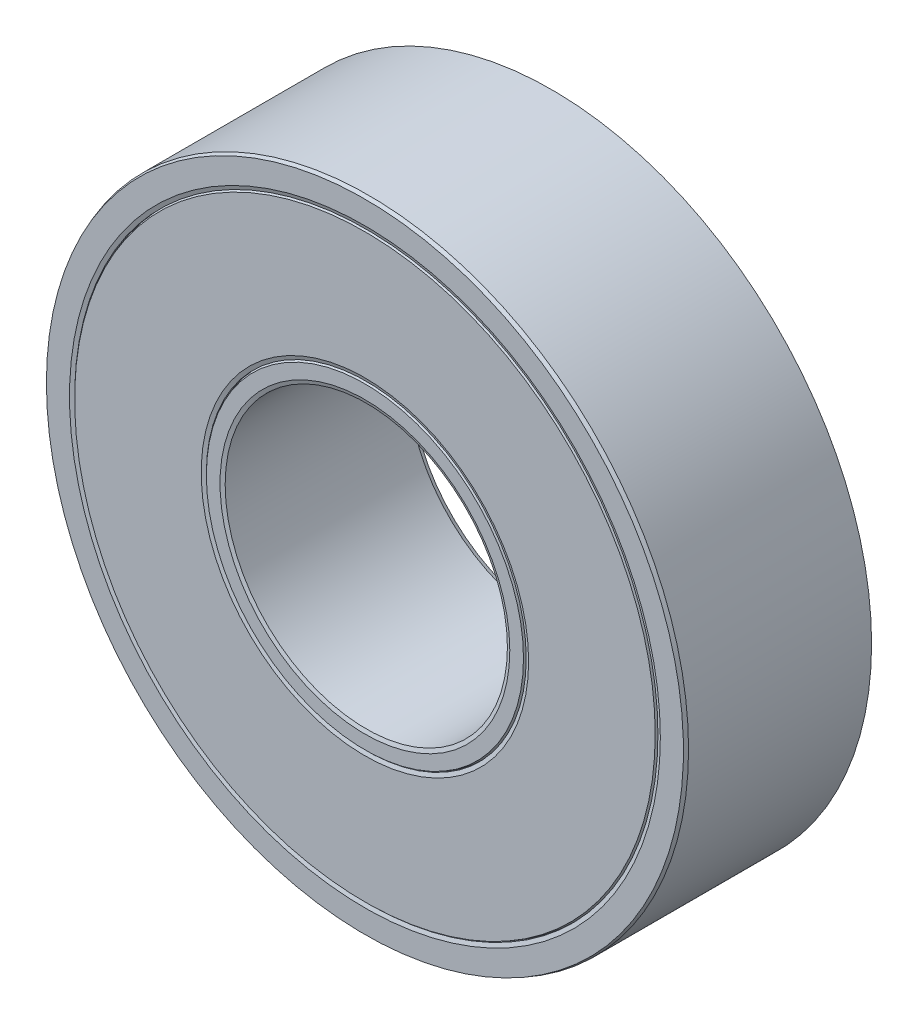
SolidWorks part; units mm, degrees
ref_plane "Front Plane" through (0, 0, 0) normal (0, 0, 1) x (1, 0, 0)
ref_plane "Top Plane" through (0, 0, 0) normal (0, 1, 0) x (1, 0, 0)
ref_plane "Right Plane" through (0, 0, 0) normal (1, 0, 0) x (0, 0, -1)
sketch "Sketch1" plane through (0, 0, 0) normal (0, 0, 1) x (1, 0, 0)
  circle A0 centre (0, 0) radius 7.5
  circle A1 centre (0, 0) radius 8.5
  dimension "D1" = 15
  dimension "D2" = 1
extrude "Boss-Extrude1" add sketch "Sketch1" along normal blind 10
sketch "Sketch2" plane through (0, 0, 10) normal (0, 0, 1) x (1, 0, 0)
  circle A0 centre (0, 0) radius 8.5
  circle A1 centre (0, 0) radius 15.5
  dimension "D2" = 31
  dimension "D1" = 17
extrude "Boss-Extrude2" add sketch "Sketch2" against normal blind 10 separate body
sketch "Sketch3" plane through (0, 0, 10) normal (0, 0, 1) x (1, 0, 0)
  circle A0 centre (0, 0) radius 15.5
  circle A1 centre (0, 0) radius 17
  dimension "D1" = 34
  dimension "D2" = 31
extrude "Boss-Extrude3" add sketch "Sketch3" against normal blind 10 separate body
chamfer "Chamfer1" distance 0.2 angle 20 4 edges at (7.5, 0, 0) (8.5, 0, 0) (7.5, 0, 10) (8.5, 0, 10)
chamfer "Chamfer2" distance 0.2 angle 20 4 edges at (15.5, 0, 0) (8.5, 0, 0) (15.5, 0, 10) (8.5, 0, 10)
chamfer "Chamfer3" distance 0.2 angle 20 4 edges at (17, 0, 0) (15.5, 0, 0) (17, 0, 10) (15.5, 0, 10)
equation "\"InnerDia\" = 15mm"
equation "\"OuterDia\" = 34mm"
equation "\"Width\"= 10mm"
equation "\"D1@Sketch1\"=\"InnerDia\""
equation "\"D1@Boss-Extrude1\"=\"Width\""
equation "\"D1@Boss-Extrude2\"=\"Width\""
equation "\"D1@Sketch3\"=\"OuterDia\""
equation "\"D2@Sketch3\"=\"OuterDia\"-3"
equation "\"D1@Boss-Extrude3\"=\"Width\""
equation "\"D1@Sketch2\"=\"InnerDia\"+0.2cm"
equation "\"D2@Sketch2\"=\"OuterDia\"-0.3cm"
